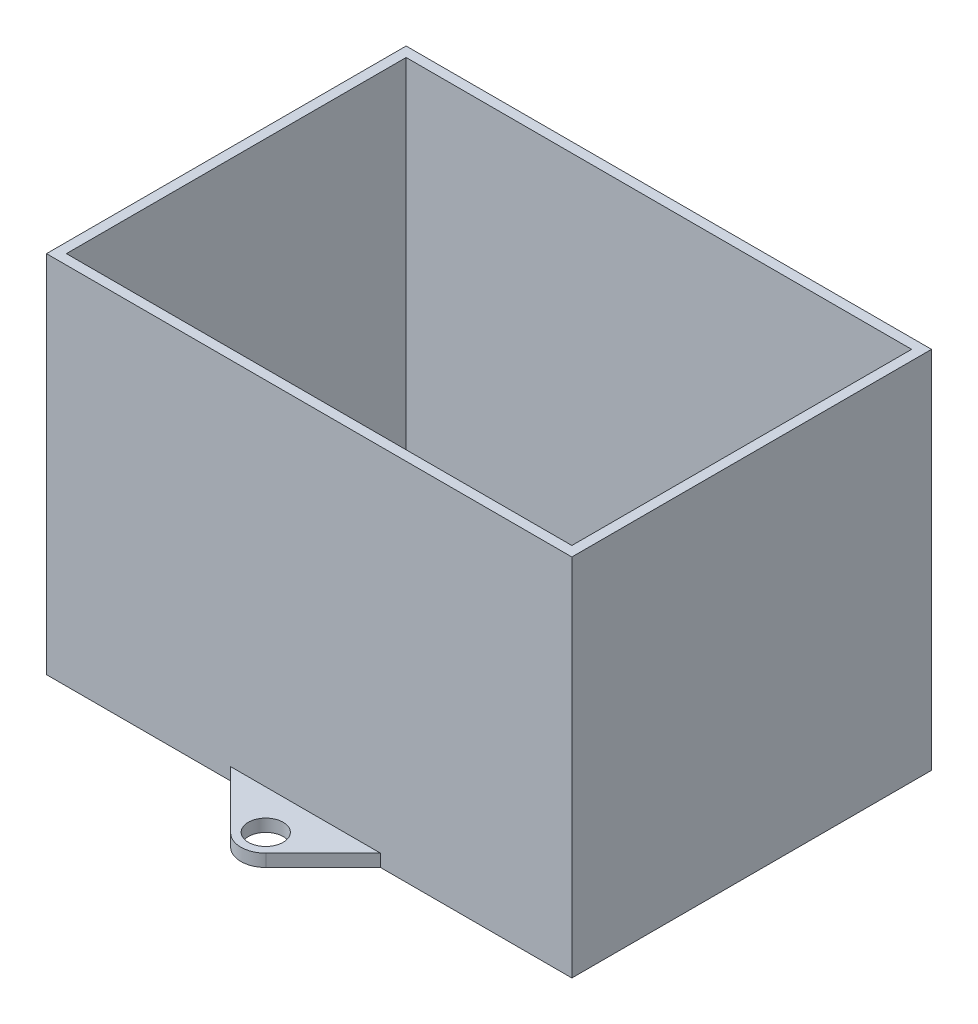
SolidWorks part; units mm, degrees
ref_plane "前视基准面" through (0, 0, 0) normal (0, 0, 1) x (1, 0, 0)
ref_plane "上视基准面" through (0, 0, 0) normal (0, 1, 0) x (1, 0, 0)
ref_plane "右视基准面" through (0, 0, 0) normal (1, 0, 0) x (0, 0, -1)
other "Configuration Table"
sketch "草图1" plane through (0, 0, 0) normal (0, 1, 0) x (1, 0, 0)
  line L1 (0, 0) -> (61, 0)
  line L2 (0, 0) -> (0, 41)
  line L3 (0, 41) -> (61, 41)
  line L4 (61, 0) -> (61, 41)
  line L8 (-1.2, -1.2) -> (-1.2, 42.2)
  line L9 (-1.2, 42.2) -> (62.2, 42.2)
  line L10 (62.2, -1.2) -> (62.2, 42.2)
  line L11 (-1.2, -1.2) -> (62.2, -1.2)
  line L13 (-7.5, -6) -> (68.5, -6)
  line L14 (-7.5, -6) -> (-7.5, 45)
  line L15 (-7.5, 45) -> (68.5, 45)
  line L16 (68.5, -6) -> (68.5, 45)
  point P13 (30.5, 45)
  point P14 (30.5, 41)
  dimension "D1" = 41
  dimension "D2" = 61
  dimension "D3" = 76
  dimension "D5" = 6
  dimension "D6" = 4
  dimension "D4" = 1.2
extrude "凸台-拉伸2" add sketch "草图1" along normal blind 44 contours L8 L11 L10 L9 L4 L1 L2 L3
sketch "草图3" plane through (0, 0, 0) normal (0, -1, 0) x (1, 0, 0)
  line L0 (62.2, 1.2) -> (62.2, -42.2) construction
  line L1 (-1.2, 1.2) -> (62.2, 1.2)
  line L2 (-1.2, 1.2) -> (-1.2, 13.2)
  line L3 (-1.2, 13.2) -> (62.2, 13.2)
  line L4 (62.2, 1.2) -> (62.2, 13.2)
  dimension "D1" = 12
extrude "凸台-拉伸3" add sketch "草图3" against normal blind 1.5
sketch "草图4" plane through (0, 1.5, 0) normal (0, 1, 0) x (1, 0, 0)
  line L0 (32.1823, -8.1213) -> (49.8599, 9.5564) construction
  line L1 (27.9396, -8.1213) -> (-21.6188, 41.4371) construction
  line L2 (32.1823, -8.1213) -> (49.8599, 9.5564)
  line L3 (27.9396, -8.1213) -> (-21.6188, 41.4371)
  line L4 (-1.2, -1.2) -> (62.2, -1.2) construction
  line L5 (-1.2, -1.2) -> (62.2, -1.2)
  line L10 (-1.2, -1.2) -> (-1.2, -13.2)
  line L11 (-1.2, -13.2) -> (62.2, -13.2)
  line L12 (62.2, -13.2) -> (62.2, -1.2)
  line L13 (62.2, -1.2) -> (-1.2, -1.2)
  line L14 (-1.2, -1.2) -> (-1.2, -13.2)
  line L15 (-1.2, -13.2) -> (62.2, -13.2)
  line L16 (62.2, -13.2) -> (62.2, -1.2)
  line L17 (62.2, -1.2) -> (-1.2, -1.2)
  circle A0 centre (30, -5.939) radius 1.5 construction
  circle A1 centre (30, -5.939) radius 1.5
  arc A2 (27.9396, -8.1213) -> (32.1823, -8.1213) centre (30.061, -6) ccw construction
  arc A3 (27.9396, -8.1213) -> (32.1823, -8.1213) centre (30.061, -6) ccw
  line M5 (-1.2, -1.2) -> (-1.2, -13.2)
  line M6 (-1.2, -13.2) -> (62.2, -13.2)
  line M7 (62.2, -13.2) -> (62.2, -1.2)
  line M8 (62.2, -1.2) -> (-1.2, -1.2)
  dimension "D1" = 0
extrude "切除-拉伸1" cut sketch "草图4" against normal blind 10 contours A3 L3 L2 M8 M5 M6 M7 | A1
sketch "草图5" plane through (-1.2, 0, 0) normal (-1, 0, 0) x (0, 0, 1)
  line L0 (8.1213, 0) -> (-41.4371, 0)
  line L1 (-42.2, 0) -> (-21.0183, 0)
  line L2 (-42.2, 0) -> (-42.2, 1.5)
  line L3 (-42.2, 1.5) -> (-21.0183, 1.5)
  line L4 (-21.0183, 0) -> (-21.0183, 1.5)
  line L6 (8.1213, 0) -> (-41.4371, 0) construction
  point P5 (0, 0)
  point P6 (0, 0)
  point P9 (0, 0)
  line M5 (-42.2, 0) -> (1.2, 0)
  line M8 (-42.2, 44) -> (-42.2, 0)
  dimension "D1" = 1.5
extrude "凸台-拉伸4" add sketch "草图5" along normal blind 26 contours L4 L3 M5 M8
sketch "草图6" plane through (0, 1.5, 0) normal (0, 1, 0) x (1, 0, 0)
  line L0 (-21.6188, 45.6797) -> (-3.9412, 63.3574) construction
  line L1 (27.9396, -8.1213) -> (-21.6188, 41.4371) construction
  line L2 (-21.6188, 45.6797) -> (-3.9412, 63.3574)
  line L3 (27.9396, -8.1213) -> (-21.6188, 41.4371)
  line L8 (-1.2, 21.0183) -> (-1.2, 42.2)
  line L9 (-1.2, 42.2) -> (-27.2, 42.2)
  line L10 (-27.2, 42.2) -> (-27.2, 21.0183)
  line L11 (-27.2, 21.0183) -> (-1.2, 21.0183)
  line L12 (-1.2, 21.0183) -> (-1.2, 42.2)
  line L13 (-1.2, 42.2) -> (-27.2, 42.2)
  line L14 (-27.2, 42.2) -> (-27.2, 21.0183)
  line L15 (-27.2, 21.0183) -> (-1.2, 21.0183)
  circle A0 centre (-19.4975, 43.5584) radius 1.5 construction
  circle A1 centre (-19.4975, 43.5584) radius 1.5
  arc A2 (-21.6188, 45.6797) -> (-21.6188, 41.4371) centre (-19.4975, 43.5584) ccw construction
  arc A3 (-21.6188, 45.6797) -> (-21.6188, 41.4371) centre (-19.4975, 43.5584) ccw
  line M6 (-1.2, 42.2) -> (-27.2, 42.2)
  line M7 (-27.2, 42.2) -> (-27.2, 21.0183)
  line M8 (-27.2, 21.0183) -> (-1.2, 21.0183)
  dimension "D1" = 0
extrude "切除-拉伸2" cut sketch "草图6" against normal blind 26 contours A3 L2 L3 M6 M7 M8 | A1
sketch "草图8" plane through (-33.6493, 0, -33.6492) normal (-0.7071, 0, -0.7071) x (-0.7071, 0, 0.7071)
  line L0 (-14.0137, 0) -> (-14.0137, 1.5) construction
  line L1 (-14.0137, 0) -> (-14.0137, 1.5)
  line L2 (-28.9914, 44) -> (-28.9914, 1.5) construction
  line L3 (-28.9914, 44) -> (-28.9914, 1.5)
  line L5 (-14.0137, 0) -> (-28.9914, 0)
  line L6 (-14.0137, 0) -> (-14.0137, 1.5)
  line L7 (-14.0137, 1.5) -> (-28.9914, 1.5)
  line L8 (-28.9914, 0) -> (-28.9914, 1.5)
  line M1 (-17.0137, 0) -> (-42.0137, 0)
extrude "凸台-拉伸5" add sketch "草图8" against normal up to vertex contours L8 L5 L1 L7 M1
sketch "草图7" plane through (0, 1.5, 0) normal (0, 1, 0) x (1, 0, 0)
  line L4 (-1.2, 21.0183) -> (-1.2, 42.2)
  line L5 (-1.2, 42.2) -> (-13.1493, 54.1493)
  line L6 (-13.1493, 54.1493) -> (-23.7402, 43.5584)
  line L7 (-23.7402, 43.5584) -> (-1.2, 21.0183)
  line L8 (-1.2, 21.0183) -> (-1.2, 42.2)
  line L9 (-1.2, 42.2) -> (-13.1493, 54.1493)
  line L10 (-13.1493, 54.1493) -> (-23.7402, 43.5584)
  line L11 (-23.7402, 43.5584) -> (-1.2, 21.0183)
  circle A1 centre (30, -5.939) radius 1.5 construction
  circle A3 centre (30, -5.939) radius 1.5
  circle A5 centre (30, -5.939) radius 2.1
  circle A6 centre (-19.4975, 43.5584) radius 1.5 construction
  circle A7 centre (-19.4975, 43.5584) radius 1.5
  circle A8 centre (-19.4975, 43.5584) radius 2.1
  arc A9 (-21.6188, 45.6797) -> (-21.6188, 41.4371) centre (-19.4975, 43.5584) ccw construction
  arc A10 (-21.6188, 45.6797) -> (-21.6188, 41.4371) centre (-19.4975, 43.5584) ccw
  dimension "D1" = 4.2
  dimension "D2" = 4.2
  dimension "D3" = 0
extrude "切除-拉伸3" cut sketch "草图7" against normal blind 26 contours A10 L10 L11 | A8 | A5
